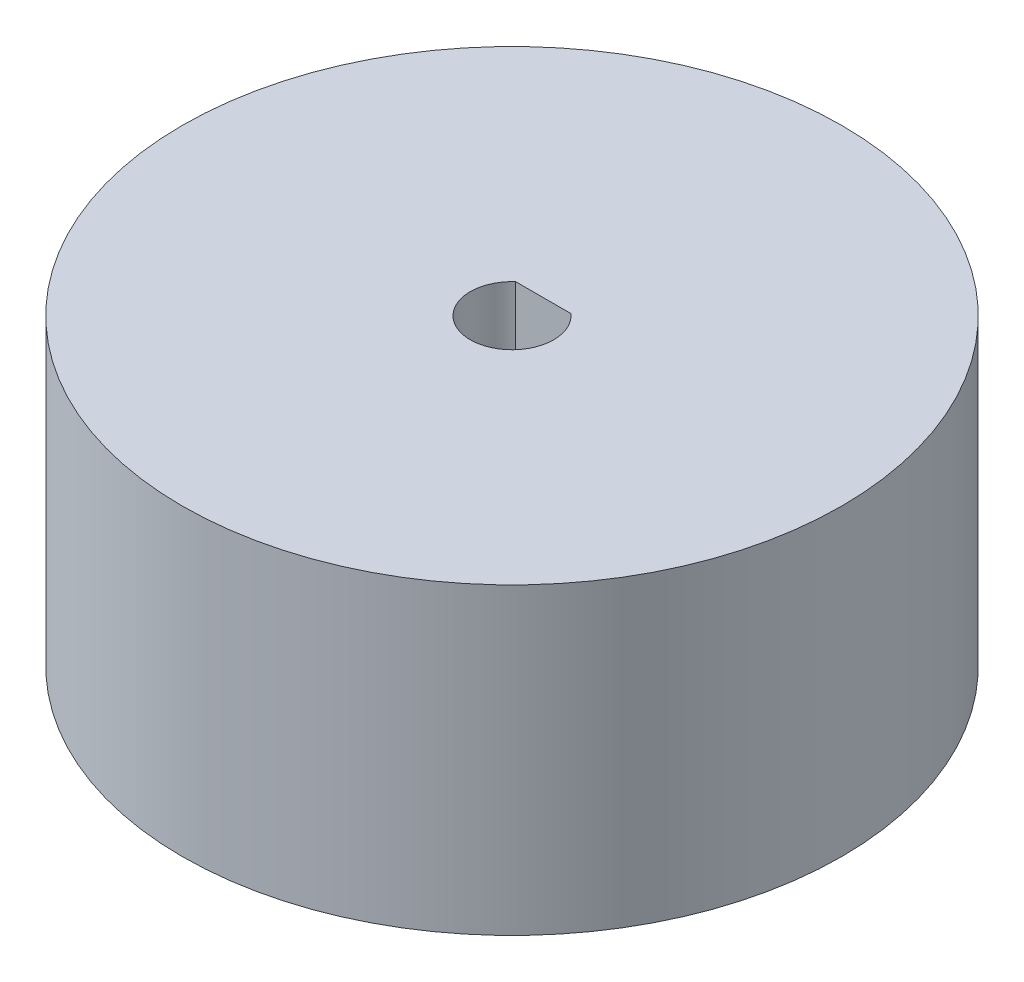
SolidWorks part; units mm, degrees
ref_plane "Front Plane" through (0, 0, 0) normal (0, 0, 1) x (1, 0, 0)
ref_plane "Top Plane" through (0, 0, 0) normal (0, 1, 0) x (1, 0, 0)
ref_plane "Right Plane" through (0, 0, 0) normal (1, 0, 0) x (0, 0, -1)
sketch "Sketch5" plane through (0, 0, 0) normal (0, 1, 0) x (1, 0, 0)
  line L1 (-1.4552, 1.65) -> (1.4552, 1.65)
  arc A0 (-1.4552, 1.65) -> (1.4552, 1.65) centre (0, 0) ccw
  circle A1 centre (0, 0) radius 17.375
  dimension "D1" = 34.75
extrude "Boss-Extrude3" add sketch "Sketch5" along normal blind 16
